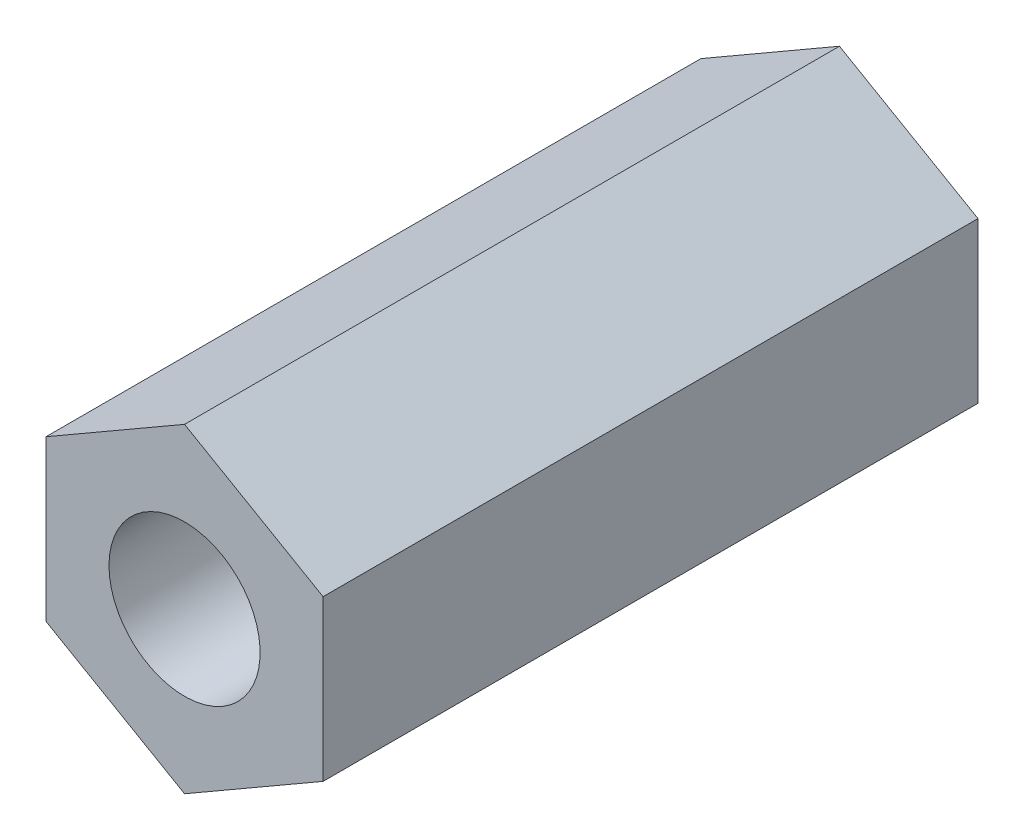
SolidWorks part; units mm, degrees
ref_plane "Plan de face" through (0, 0, 0) normal (0, 0, 1) x (1, 0, 0)
ref_plane "Plan de dessus" through (0, 0, 0) normal (0, 1, 0) x (1, 0, 0)
ref_plane "Plan de droite" through (0, 0, 0) normal (1, 0, 0) x (0, 0, -1)
sketch "Esquisse1" plane through (0, 0, 0) normal (0, 0, 1) x (1, 0, 0)
  line L1 (0, -3.1754) -> (2.75, -1.5877)
  line L2 (2.75, -1.5877) -> (2.75, 1.5877)
  line L3 (2.75, 1.5877) -> (0, 3.1754)
  line L4 (0, 3.1754) -> (-2.75, 1.5877)
  line L5 (-2.75, 1.5877) -> (-2.75, -1.5877)
  line L6 (-2.75, -1.5877) -> (0, -3.1754)
  circle A0 centre (0, 0) radius 2.75 construction
  circle A1 centre (0, 0) radius 1.5
  dimension "D2" = 3
  dimension "D1" = 5.5
extrude "Boss.-Extru.1" add sketch "Esquisse1" along normal blind 13
